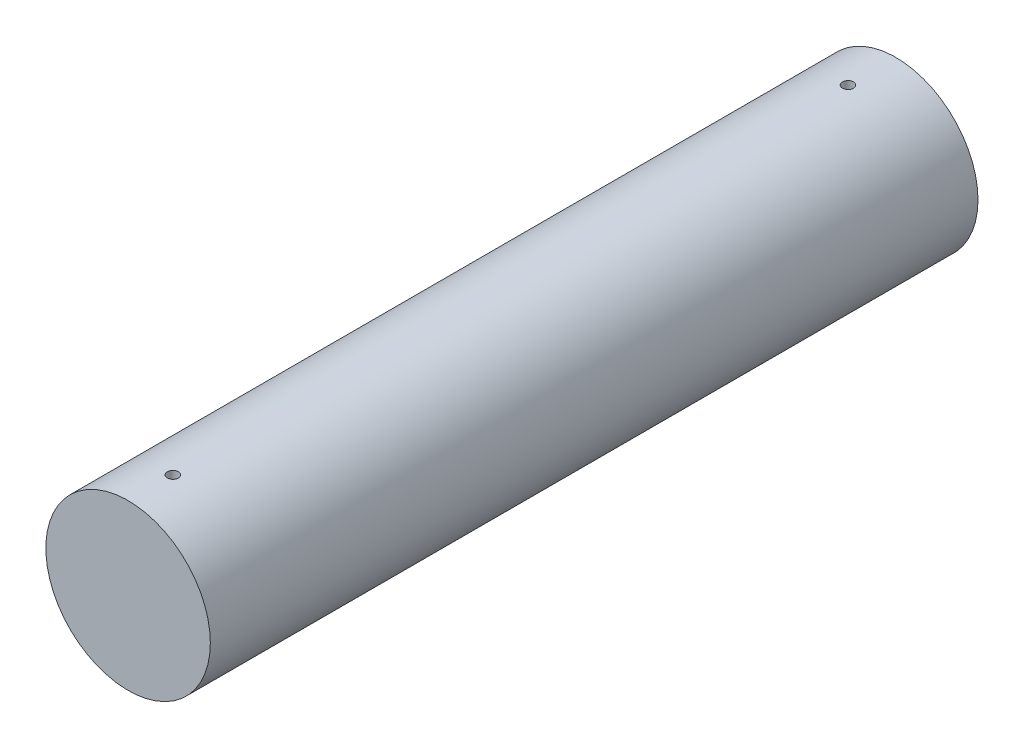
SolidWorks part; units mm, degrees
material "Lega 1060"
ref_plane "Piano frontale" through (0, 0, 0) normal (0, 0, 1) x (1, 0, 0)
ref_plane "Piano superiore" through (0, 0, 0) normal (0, 1, 0) x (1, 0, 0)
ref_plane "Piano destro" through (0, 0, 0) normal (1, 0, 0) x (0, 0, -1)
sketch "Schizzo1" plane through (0, 0, 0) normal (0, 0, 1) x (1, 0, 0)
  circle A0 centre (0, 0) radius 75
  dimension "D1" = 150
extrude "Estrusione-Estrusione1" add sketch "Schizzo1" along normal blind 700
sketch "Schizzo2" plane through (0, 0, 0) normal (0, 1, 0) x (1, 0, 0)
  circle A0 centre (0, -43.6322) radius 5
  circle A1 centre (0, -646.7185) radius 5
  dimension "D1" = 10
  dimension "D2" = 10
extrude "Taglio-Estrusione1" cut sketch "Schizzo2" against normal through all both and the other way through all contours A0
sketch "Schizzo3" plane through (0, 0, 0) normal (0, 1, 0) x (1, 0, 0)
  circle A0 centre (0, -659.2627) radius 5
  dimension "D1" = 10
extrude "Taglio-Estrusione2" cut sketch "Schizzo3" against normal through all both and the other way through all
